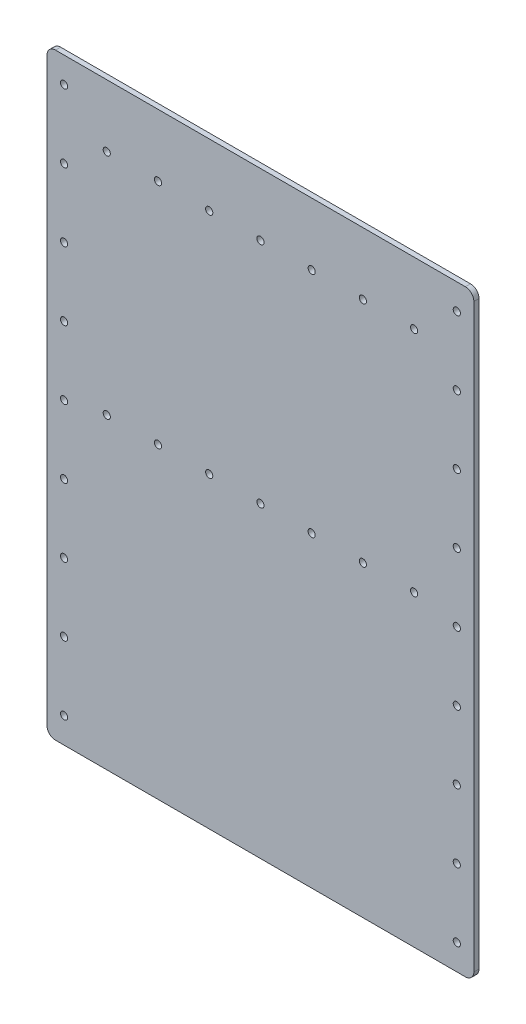
SolidWorks part; units mm, degrees
material "Thornel Mat VMA"
ref_plane "Front Plane" through (0, 0, 0) normal (0, 0, 1) x (1, 0, 0)
ref_plane "Top Plane" through (0, 0, 0) normal (0, 1, 0) x (1, 0, 0)
ref_plane "Right Plane" through (0, 0, 0) normal (1, 0, 0) x (0, 0, -1)
sketch "Sketch1" plane through (0, 0, 0) normal (0, 0, 1) x (1, 0, 0)
  line L1 (-125, -175) -> (125, -175)
  line L2 (-125, -175) -> (-125, 175)
  line L3 (-125, 175) -> (125, 175)
  line L4 (125, -175) -> (125, 175)
  line L5 (-125, -175) -> (125, 175) construction
  line L6 (-125, 175) -> (125, -175) construction
  point P0 (0, 0)
  dimension "D1" = 250
  dimension "D2" = 350
extrude "Boss-Extrude1" add sketch "Sketch1" along normal blind 3
sketch "Sketch2" plane through (0, 0, 0) normal (0, 0, -1) x (-1, 0, 0)
  line L1 (-125, 175) -> (-105, 175)
  line L2 (-125, 175) -> (-125, 635)
  line L3 (-125, 635) -> (-105, 635)
  line L4 (-105, 175) -> (-105, 635)
  dimension "D1" = 20
  dimension "D2" = 460
sketch "Sketch3" plane through (0, 0, 0) normal (0, 0, -1) x (-1, 0, 0)
  line L0 (-115, 175) -> (-115, -175) construction
  line L1 (-125, 175) -> (-105, 175) construction
  line L2 (125, -175) -> (-125, -175) construction
  circle A0 centre (-115, 160) radius 2.1
  circle A1 centre (-115, 120) radius 2.1
  circle A2 centre (-115, 80) radius 2.1
  circle A3 centre (-115, 40) radius 2.1
  circle A4 centre (-115, 0) radius 2.1
  circle A5 centre (-115, -40) radius 2.1
  circle A6 centre (-115, -80) radius 2.1
  circle A7 centre (-115, -120) radius 2.1
  circle A8 centre (-115, -160) radius 2.1
  dimension "D1" = 4.2
  dimension "D2" = 15
  dimension "D4" = 15
  dimension "D3" = 9
extrude "Cut-Extrude1" cut sketch "Sketch3" against normal through all
mirror "Mirror1" about plane through (0, 0, 0) normal (1, 0, 0) of "Cut-Extrude1"
fillet "Fillet1" radius 5 4 edges at (125, -175, 1.5) (-125, -175, 1.5) (-125, 175, 1.5) (125, 175, 1.5)
sketch "Sketch4" plane through (0, 0, 0) normal (0, 0, -1) x (-1, 0, 0)
  line L0 (0, 175) -> (0, 138.5) construction
  line L1 (-120, 175) -> (120, 175) construction
  line L2 (-90, 138.5) -> (90, 138.5) construction
  circle A0 centre (-90, 138.5) radius 2.1
  circle A1 centre (-115, 160) radius 2.1 construction
  circle A2 centre (-60, 138.5) radius 2.1
  circle A3 centre (-30, 138.5) radius 2.1
  circle A4 centre (0, 138.5) radius 2.1
  circle A5 centre (30, 138.5) radius 2.1
  circle A6 centre (60, 138.5) radius 2.1
  circle A7 centre (90, 138.5) radius 2.1
  point P10 (0, 138.5)
  dimension "D2" = 4.2
  dimension "D3" = 25
  dimension "D5" = 30
  dimension "D1" = 36.5
  dimension "D4" = 7
extrude "Cut-Extrude2" cut sketch "Sketch4" against normal through all
pattern_linear "LPattern1" count 2 spacing 133.5 along (0, -1, 0) of "Cut-Extrude2"
